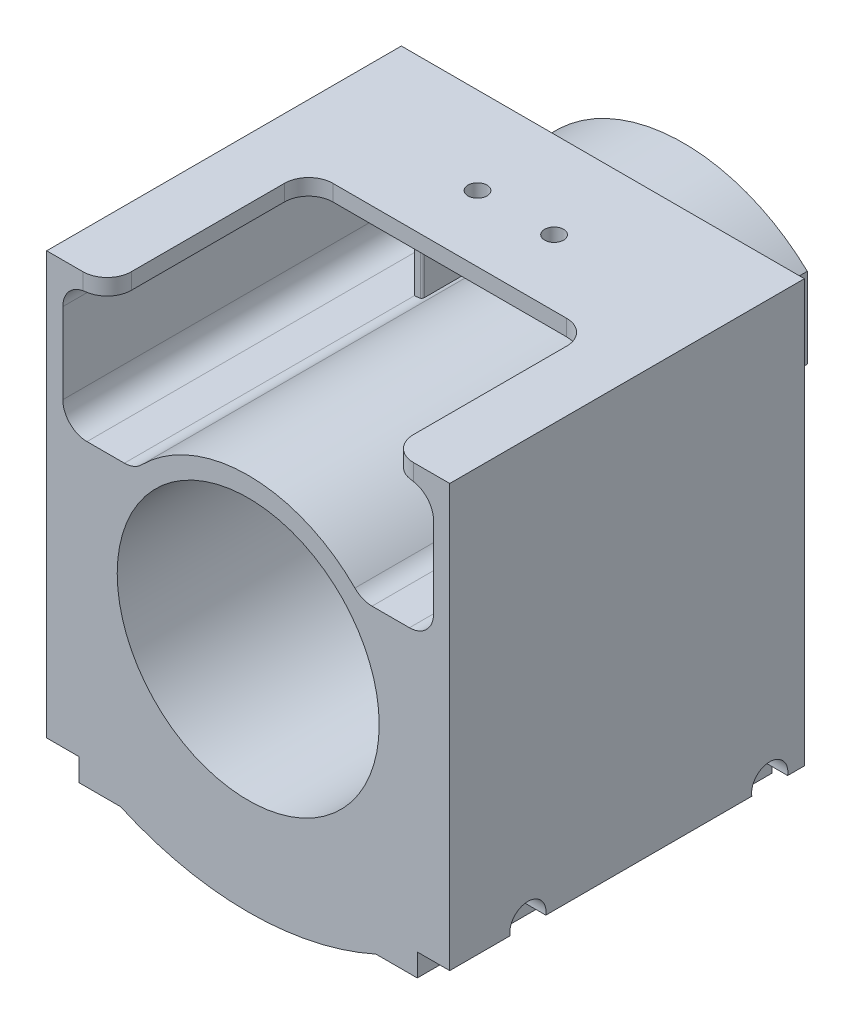
SolidWorks part; units mm, degrees
ref_plane "Front Plane" through (0, 0, 0) normal (0, 0, 1) x (1, 0, 0)
ref_plane "Top Plane" through (0, 0, 0) normal (0, 1, 0) x (1, 0, 0)
ref_plane "Right Plane" through (0, 0, 0) normal (1, 0, 0) x (0, 0, -1)
sketch "Sketch1" plane through (0, 0, 0) normal (0, 0, 1) x (1, 0, 0)
  line L1 (0, 0) -> (0, -38.55) construction
  line L2 (-25, 0) -> (-25, -29.3445)
  line L3 (25, 0) -> (25, -29.3445)
  line L4 (-25, 0) -> (-25, 20)
  line L5 (-25, 20) -> (25, 20)
  line L6 (25, 20) -> (25, 0)
  line L7 (25, -29.3445) -> (25, -32.3445)
  line L8 (25, -32.3445) -> (20.9746, -32.3445)
  line L9 (20.9746, -32.3445) -> (20.9746, -35.1445)
  line L10 (20.9746, -35.1445) -> (15.8418, -35.1445)
  line L11 (-20.9746, -35.1445) -> (-15.8418, -35.1445)
  line L12 (-20.9746, -32.3445) -> (-20.9746, -35.1445)
  line L13 (-25, -32.3445) -> (-20.9746, -32.3445)
  line L14 (-25, -29.3445) -> (-25, -32.3445)
  arc A0 (-25, -29.3445) -> (-20.9746, -32.3445) centre (0, 0) ccw construction
  arc A1 (20.9746, -32.3445) -> (25, -29.3445) centre (0, 0) ccw construction
  arc A2 (15.8418, -35.1445) -> (20.9746, -32.3445) centre (0, 0) ccw construction
  arc A3 (-15.8418, -35.1445) -> (15.8418, -35.1445) centre (0, 0) ccw
  arc A4 (-20.9746, -32.3445) -> (-15.8418, -35.1445) centre (0, 0) ccw construction
  dimension "D1" = 77.1
  dimension "D2" = 50
  dimension "D3" = 20
  dimension "D4" = 3
  dimension "D5" = 2.8
extrude "Boss-Extrude2" add sketch "Sketch1" along normal blind 44 from offset 6
sketch "Sketch2" plane through (0, 0, 50) normal (0, 0, 1) x (1, 0, 0)
  line L6 (0, 5.95) -> (0, -26.55) construction
  circle A0 centre (0, -10.3) radius 16.25
  dimension "D2" = 32.5
  dimension "D1" = 10.3
extrude "Cut-Extrude1" cut sketch "Sketch2" against normal through all both
sketch "Sketch4" plane through (0, 0, 50) normal (0, 0, 1) x (1, 0, 0)
  line L0 (-23, 18) -> (23, 18)
  line L3 (0, 20) -> (0, 5.95) construction
  line L4 (25, 20) -> (-25, 20) construction
  line L5 (23, 2) -> (14.0609, 2)
  line L6 (-23, 18) -> (-23, 2)
  line L7 (-23, 2) -> (-14.0609, 2)
  line L8 (-25, 20) -> (-25, -32.3445) construction
  line L9 (23, 18) -> (23, 2)
  circle A2 centre (0, -10.3) radius 16.25 construction
  arc A3 (14.0609, 2) -> (-14.0609, 2) centre (0, -10.3) ccw
  point P2 (0, 12.975)
  point P14 (0, 18)
  dimension "D1" = 37.3631
  dimension "D2" = 2
  dimension "D3" = 2
  dimension "D4" = 16
extrude "Cut-Extrude3" cut sketch "Sketch4" against normal through all
fillet "Fillet1" radius 3 6 edges at (23, 18, 28) (23, 2, 28) (14.0609, 2, 28) (-14.0609, 2, 28) (-23, 2, 28) (-23, 18, 28)
sketch "Sketch5" plane through (0, 20, 0) normal (0, 1, 0) x (1, 0, 0)
  line L0 (25, -50) -> (-25, -50) construction
  line L1 (-17.5, -50) -> (17.5, -50)
  line L2 (-17.5, -50) -> (-17.5, -25)
  line L3 (-17.5, -25) -> (17.5, -25)
  line L4 (17.5, -50) -> (17.5, -25)
  line L5 (0, 0) -> (0, -50) construction
  dimension "D1" = 35
  dimension "D2" = 25
extrude "Cut-Extrude4" cut sketch "Sketch5" against normal blind 10
fillet "Fillet2" radius 3 4 edges at (17.5, 19, 50) (17.5, 19, 25) (-17.5, 19, 25) (-17.5, 19, 50)
ref_plane "Plane1" through (0, 0, 14) normal (0, 0, 1) x (1, 0, 0)
sketch "Sketch6" plane through (0, 0, 14) normal (0, 0, 1) x (1, 0, 0)
  line L0 (0, -10.3) -> (0, 2.7) construction
  line L1 (0, -10.3) -> (4.4463, 1.916) construction
  circle A1 centre (0, -10.3) radius 16.25 construction
  circle A3 centre (0, -10.3) radius 9.5
  circle A8 centre (0, -10.3) radius 16.25
  circle A9 centre (0, -10.3) radius 13 construction
  circle A10 centre (4.4463, 1.916) radius 1.65
  circle A11 centre (12.216, -14.7463) radius 1.65
  circle A12 centre (-4.4463, -22.516) radius 1.65
  circle A13 centre (-12.216, -5.8537) radius 1.65
  dimension "D1" = 19
  dimension "D6" = 13
  dimension "D2" = 3.5
  dimension "D3" = 3.3
  dimension "D4" = 20
  dimension "D5" = 4
extrude "Boss-Extrude3" add sketch "Sketch6" against normal blind 5
sketch "Sketch7" plane through (0, 0, 0) normal (1, 0, 0) x (0, 0, -1)
  circle A0 centre (-40.3, -32) radius 2.25
  circle A1 centre (-10.3, -32) radius 2.25
  dimension "D3" = 4.5
  dimension "D1" = 32
  dimension "D2" = 10.3
  dimension "D4" = 30
extrude "Cut-Extrude5" cut sketch "Sketch7" against normal through all both and the other way through all
sketch "Sketch8" plane through (0, 20, 0) normal (0, 1, 0) x (1, 0, 0)
  line L0 (0, -6) -> (0, -25) construction
  line L1 (25, -6) -> (-25, -6) construction
  line L2 (14.5, -25) -> (-14.5, -25) construction
  circle A0 centre (-4.75, -16.8) radius 1.175
  circle A1 centre (4.75, -16.8) radius 1.175
  dimension "D1" = 2.35
  dimension "D2" = 9.5
  dimension "D3" = 10.8
extrude "Cut-Extrude6" cut sketch "Sketch8" against normal up to next contours A0 | A1
sketch "Sketch9" plane through (0, 0, 50) normal (0, 0, 1) x (1, 0, 0)
  line L0 (0, -28.8) -> (0, -5.3) construction
  line L1 (0, -10.3) -> (0, -28.8) construction
  line L2 (-15.3623, 2) -> (-15.3623, 10.9768)
  line L3 (15.3623, 2) -> (15.3623, 10.9768)
  line L4 (0, 8.3815) -> (0, 17.0815) construction
  line L5 (-14.3623, 2.1716) -> (-14.3623, 10.0902)
  line L6 (14.3623, 2.1716) -> (14.3623, 10.0902)
  line L7 (-15.3623, 2) -> (-15.3623, 1)
  line L8 (15.3623, 2) -> (15.3623, 1)
  line L9 (14.3623, 2) -> (14.3623, 10.5397) construction
  line L10 (-14.3623, 2) -> (-14.3623, 10.5397) construction
  arc A0 (13.2366, 2.883) -> (-13.2366, 2.883) centre (0, -10.3) ccw construction
  arc A1 (13.2366, 2.883) -> (-13.2366, 2.883) centre (0, -10.3) ccw
  arc A3 (-15.3623, 10.9768) -> (15.3623, 10.9768) centre (0, -5.3) cw
  arc A4 (13.2366, 2.883) -> (15.3623, 2) centre (15.3623, 5) ccw construction
  arc A5 (-15.3623, 2) -> (-13.2366, 2.883) centre (-15.3623, 5) ccw construction
  arc A6 (13.2366, 2.883) -> (15.3623, 2) centre (15.3623, 5) ccw
  arc A7 (-15.3623, 2) -> (-13.2366, 2.883) centre (-15.3623, 5) ccw
  arc A8 (12.5281, 2.1773) -> (15.3623, 1) centre (15.3623, 5) ccw
  arc A9 (12.5281, 2.1773) -> (-12.5281, 2.1773) centre (0, -10.3) ccw
  arc A10 (-15.3623, 1) -> (-12.5281, 2.1773) centre (-15.3623, 5) ccw
  arc A11 (-14.0179, 10.8453) -> (14.0179, 10.8453) centre (0, -5.3) cw
  arc A12 (-14.3623, 10.5397) -> (14.3623, 10.5397) centre (0, -5.3) cw construction
  arc A13 (14.3623, 10.0902) -> (14.0179, 10.8453) centre (13.3623, 10.0902) ccw
  arc A14 (-14.3623, 10.0902) -> (-14.0179, 10.8453) centre (-13.3623, 10.0902) cw
  dimension "D1" = 8.7
  dimension "D2" = 1
  dimension "D4" = 1
  dimension "Ring Gear Outer Dia to Center" = 23.5
  dimension "Pinion to Ring Gear Outer Diameter" = 18.5
  dimension "D3" = 1
extrude "Boss-Extrude4" add sketch "Sketch9" along normal blind 8 and the other way blind 10 from surface at -44 contours L5 A11 L6 L2 L3 A3 A6 | L7 A10 A9 A8 L8 L2 L3 A6
fillet "Fillet5" radius 0.25 8 edges at (13.7595, 2.464, -4) (-13.7595, 2.464, -4) (14.3623, 6.1309, -4) (14.2721, 10.5051, -4) (-14.3623, 6.1309, -4) (-14.2721, 10.5051, -4) (0, 8.3815, -4) (0, 16.0815, -4)
fillet "Fillet6" radius 0.25 5 edges at (14.3623, 6.1309, 14) (14.2721, 10.5051, 14) (-14.3623, 6.1309, 14) (-14.2721, 10.5051, 14) (0, 16.0815, 14)
